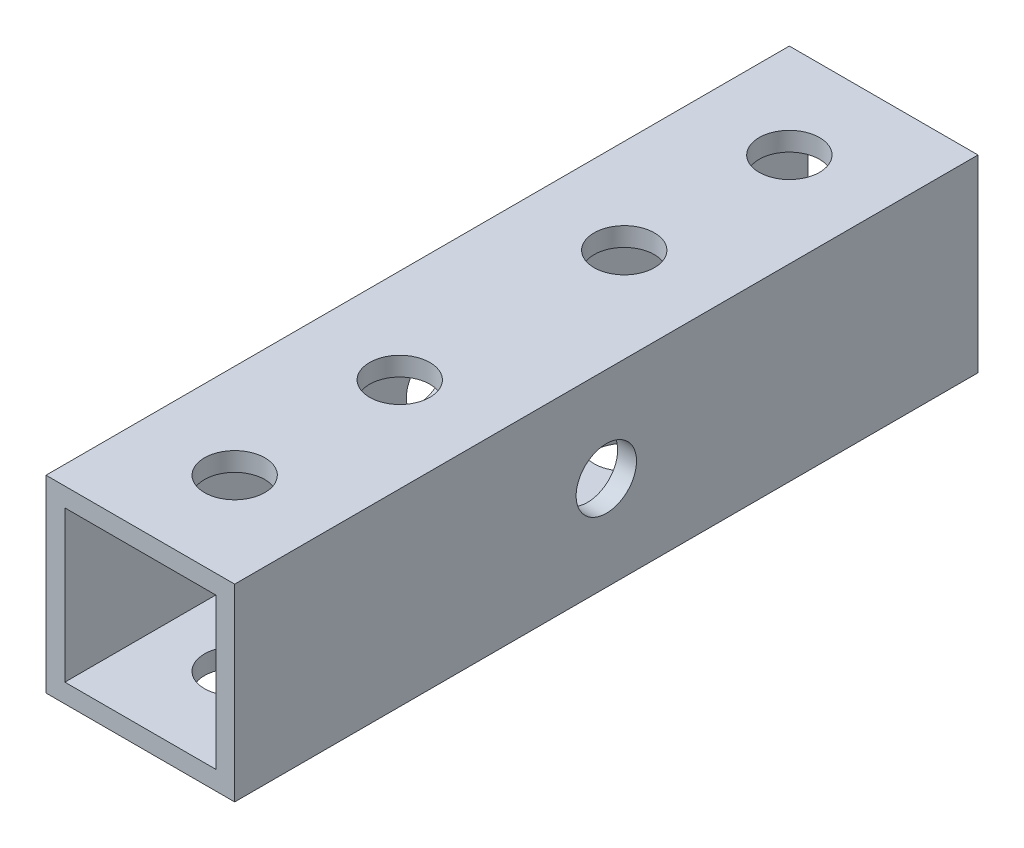
SolidWorks part; units mm, degrees
material "1060 合金"
ref_plane "正面" through (0, 0, 0) normal (0, 0, 1) x (1, 0, 0)
ref_plane "平面" through (0, 0, 0) normal (0, 1, 0) x (1, 0, 0)
ref_plane "右側面" through (0, 0, 0) normal (1, 0, 0) x (0, 0, -1)
sketch "ｽｹｯﾁ1" plane through (0, 0, 0) normal (0, 0, 1) x (1, 0, 0)
  line L1 (-5, -5) -> (5, -5)
  line L2 (-5, -5) -> (-5, 5)
  line L3 (-5, 5) -> (5, 5)
  line L4 (5, -5) -> (5, 5)
  line L5 (-5, -5) -> (5, 5) construction
  line L6 (-5, 5) -> (5, -5) construction
  point P0 (0, 0)
  dimension "10" = 10
extrude "押し出し-薄板1" add sketch "ｽｹｯﾁ1" along normal blind 39.4 thin thin type one direction reverse wall 1
sketch "ｽｹｯﾁ2" plane through (0, 5, 0) normal (0, 1, 0) x (1, 0, 0)
  line L0 (0, 0) -> (0, -39.4) construction
  line L1 (5, 0) -> (-5, 0) construction
  line L2 (5, -39.4) -> (-5, -39.4) construction
  line L3 (-5, -19.7) -> (5, -19.7) construction
  line L4 (-5, -39.4) -> (-5, 0) construction
  line L5 (5, -39.4) -> (5, 0) construction
  circle A0 centre (0, -5) radius 1.6
  circle A1 centre (0, -34.4) radius 1.6
  dimension "D1" = 3.2
  dimension "D2" = 5
extrude "ｶｯﾄ - 押し出し1" cut sketch "ｽｹｯﾁ2" against normal through all
sketch "ｽｹｯﾁ3" plane through (0, 5, 0) normal (0, 1, 0) x (1, 0, 0)
  line L0 (0, 0) -> (0, -39.4) construction
  line L1 (5, -39.4) -> (-5, -39.4) construction
  line L2 (5, 0) -> (-5, 0) construction
  line L3 (-5, -19.7) -> (5, -19.7) construction
  line L4 (-5, -39.4) -> (-5, 0) construction
  line L5 (5, -39.4) -> (5, 0) construction
  circle A0 centre (0, -13.75) radius 1.6
  circle A1 centre (0, -5) radius 1.6 construction
  circle A2 centre (0, -25.65) radius 1.6
  dimension "D1" = 13.75
extrude "ｶｯﾄ - 押し出し2" cut sketch "ｽｹｯﾁ3" against normal through all
sketch "ｽｹｯﾁ4" plane through (5, 0, 0) normal (1, 0, 0) x (0, 0, -1)
  line L0 (-39.4, 0) -> (0, 0) construction
  line L1 (-39.4, -5) -> (-39.4, 5) construction
  circle A0 centre (-19.7, 0) radius 1.6
  dimension "D1" = 3.2
extrude "ｶｯﾄ - 押し出し3" cut sketch "ｽｹｯﾁ4" against normal through all
